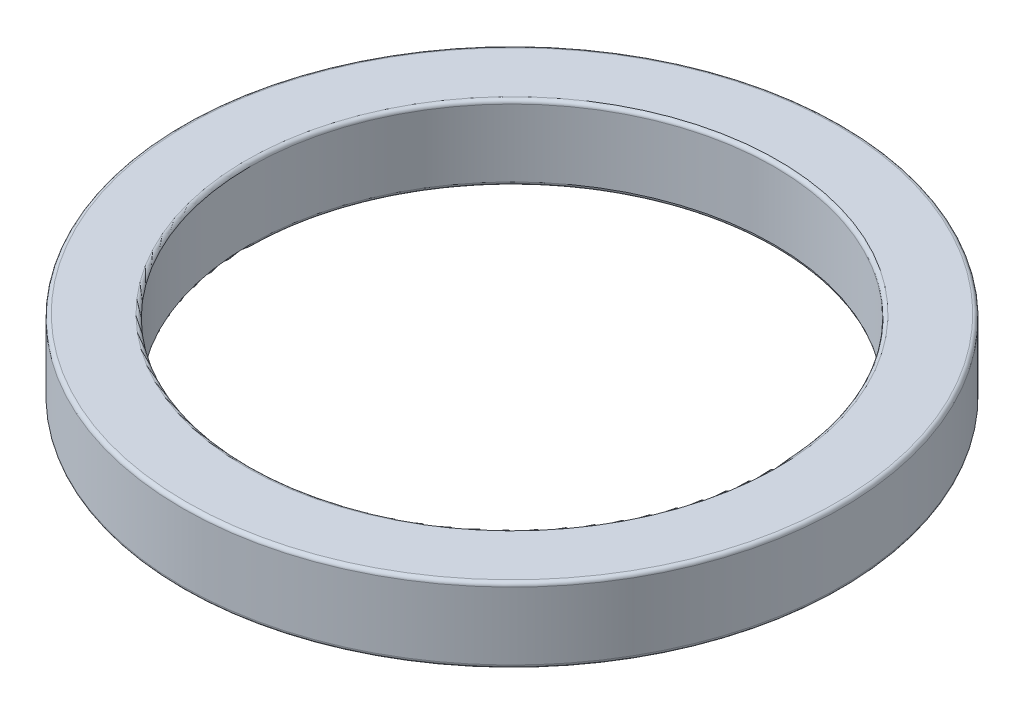
SolidWorks part; units mm, degrees
ref_plane "前视基准面" through (0, 0, 0) normal (0, 0, 1) x (1, 0, 0)
ref_plane "上视基准面" through (0, 0, 0) normal (0, 1, 0) x (1, 0, 0)
ref_plane "右视基准面" through (0, 0, 0) normal (1, 0, 0) x (0, 0, -1)
other "Configuration Table"
sketch "草图1" plane through (0, 0, 0) normal (0, 1, 0) x (1, 0, 0)
  circle A0 centre (0, 0) radius 22
  circle A1 centre (0, 0) radius 17.5
  dimension "D1" = 35
  dimension "D2" = 44
extrude "凸台-拉伸1" add sketch "草图1" along normal blind 5
fillet "圆角1" radius 0.25 4 edges at (0, 0, 17.5) (0, 5, 17.5) (0, 0, 22) (0, 5, 22)
